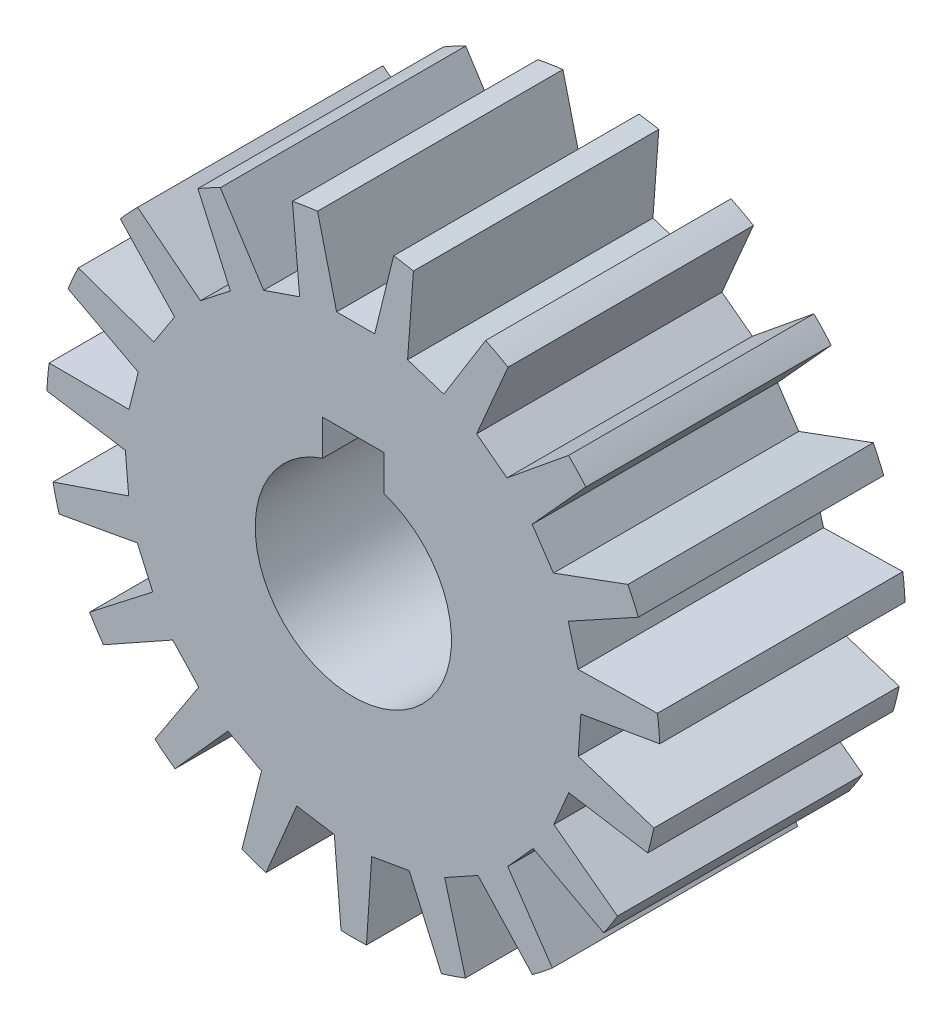
SolidWorks part; units mm, degrees
ref_plane "Alzado" through (0, 0, 0) normal (0, 0, 1) x (1, 0, 0)
ref_plane "Planta" through (0, 0, 0) normal (0, 1, 0) x (1, 0, 0)
ref_plane "Vista lateral" through (0, 0, 0) normal (1, 0, 0) x (0, 0, -1)
sketch "Croquis1" plane through (0, 0, 0) normal (0, 0, 1) x (1, 0, 0)
  circle A0 centre (0, 0) radius 12.5
  dimension "D1" = 25
extrude "Saliente-Extruir1" add sketch "Croquis1" along normal blind 10
sketch "Croquis2" plane through (0, 0, 0) normal (0, 0, -1) x (-1, 0, 0)
  line L0 (-1.669, 12.5) -> (-0.8711, 9.25)
  line L1 (-0.8711, 9.25) -> (0.681, 9.25)
  line L2 (0.681, 9.25) -> (1.4789, 12.5)
  line L3 (1.4789, 12.5) -> (-1.669, 12.5)
  line L4 (-0.095, 12.5) -> (-0.095, 9.25) construction
  line L5 (-1.27, 10.875) -> (1.08, 10.875) construction
  circle A0 centre (0, 0) radius 12.5 construction
  dimension "D1" = 3.25
  dimension "D2" = 1.625
  dimension "D3" = 1.5521
  dimension "D4" = 2.35
extrude "Cortar-Extruir1" cut sketch "Croquis2" against normal through all
pattern_circular "MatrizC1" count 19 every 19 about axis through (0, 0, 0) along (0, 0, 1) of "Cortar-Extruir1"
sketch "Croquis3" plane through (0, 0, 0) normal (0, 0, -1) x (-1, 0, 0)
  line L2 (-1.25, 3.7997) -> (-1.25, 5.25)
  line L3 (-1.25, 5.25) -> (1.25, 5.25)
  line L4 (1.25, 3.7997) -> (1.25, 5.25)
  arc A0 (-1.25, 3.7997) -> (1.25, 3.7997) centre (0, 0) ccw
  point P3 (0, 4)
  dimension "D3" = 8
  dimension "D1" = 2.5
extrude "Cortar-Extruir2" cut sketch "Croquis3" against normal blind 10
